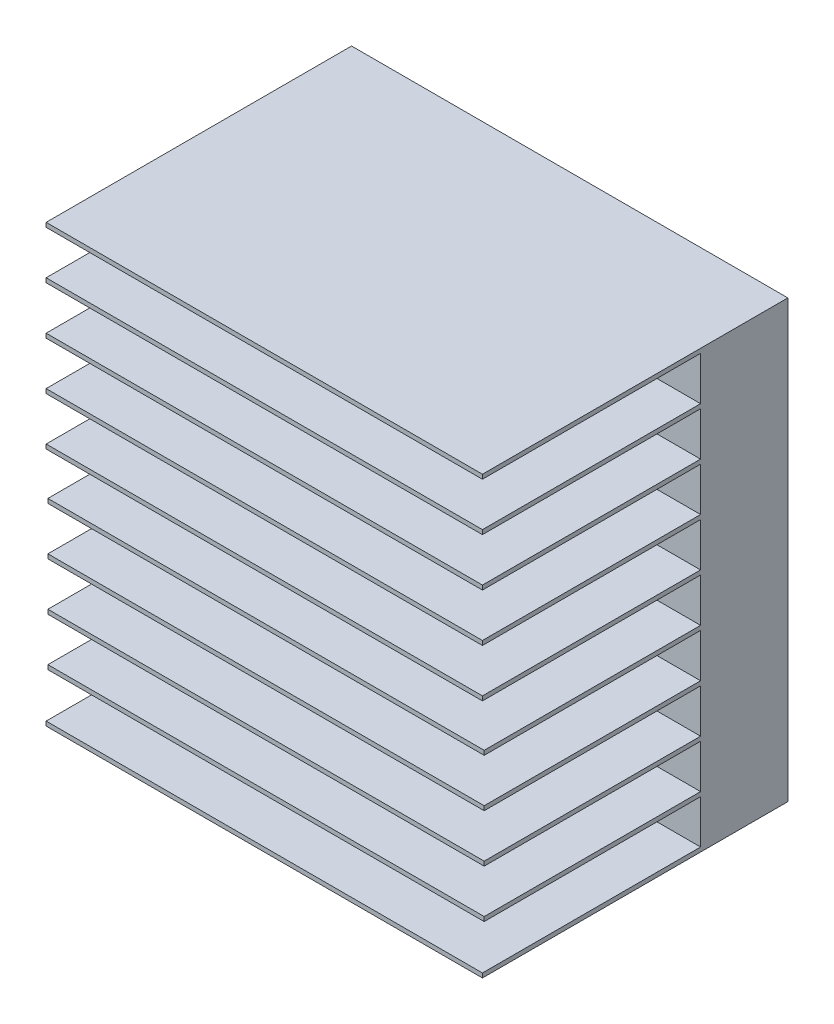
SolidWorks part; units mm, degrees
ref_plane "Front Plane" through (0, 0, 0) normal (0, 0, 1) x (1, 0, 0)
ref_plane "Top Plane" through (0, 0, 0) normal (0, 1, 0) x (1, 0, 0)
ref_plane "Right Plane" through (0, 0, 0) normal (1, 0, 0) x (0, 0, -1)
sketch "Sketch2" plane through (0, 0, 0) normal (0, 0, 1) x (1, 0, 0)
  line L1 (0, 0) -> (25.4, 0)
  line L2 (0, 0) -> (0, 25.4)
  line L3 (0, 25.4) -> (25.4, 25.4)
  line L4 (25.4, 0) -> (25.4, 25.4)
  dimension "D1" = 25.4
  dimension "D2" = 25.4
extrude "Boss-Extrude1" add sketch "Sketch2" along normal blind 5.08
sketch "Sketch3" plane through (0, 0, 5.08) normal (0, 0, 1) x (1, 0, 0)
  line L0 (25.4, 0) -> (25.4, 25.4) construction
  line L1 (0, 25.4) -> (25.4, 25.4)
  line L2 (0, 25.4) -> (0, 25.146)
  line L3 (0, 25.146) -> (25.4, 25.146)
  line L4 (25.4, 25.4) -> (25.4, 25.146)
  dimension "D1" = 0.254
extrude "Boss-Extrude2" add sketch "Sketch3" along normal blind 12.7
sketch "Sketch4" plane through (0, 0, 5.08) normal (0, 0, 1) x (1, 0, 0)
  line L0 (25.4, 0) -> (25.4, 25.146) construction
  line L1 (0, 25.146) -> (0, 0) construction
  line L2 (0, 0) -> (25.4, 0)
  line L3 (0, 0) -> (0, 0.254)
  line L4 (0, 0.254) -> (25.4, 0.254)
  line L5 (25.4, 0) -> (25.4, 0.254)
  line L6 (0, 22.606) -> (25.4, 22.606)
  line L7 (0, 22.606) -> (0, 22.352)
  line L8 (0, 22.352) -> (25.4, 22.352)
  line L9 (25.4, 22.606) -> (25.4, 22.352)
  line L11 (0, 25.146) -> (25.4, 25.146) construction
  dimension "D1" = 0.254
  dimension "D2" = 0.254
  dimension "D3" = 2.54
sketch "Sketch5" plane through (0, 0, 5.08) normal (0, 0, 1) x (1, 0, 0)
  line L0 (0, 25.146) -> (0, 0) construction
  line L1 (0, 19.812) -> (25.4, 19.812)
  line L2 (0, 19.812) -> (0, 19.558)
  line L3 (0, 19.558) -> (25.4, 19.558)
  line L4 (25.4, 19.812) -> (25.4, 19.558)
  line L5 (25.4, 0) -> (25.4, 25.146) construction
  line L7 (0, 17.018) -> (25.4, 17.018)
  line L8 (0, 17.018) -> (0, 16.764)
  line L9 (0, 16.764) -> (25.4, 16.764)
  line L10 (25.4, 17.018) -> (25.4, 16.764)
  line L11 (0, 14.224) -> (25.4, 14.224)
  line L12 (0, 14.224) -> (0, 13.97)
  line L13 (0, 13.97) -> (25.4, 13.97)
  line L14 (25.4, 14.224) -> (25.4, 13.97)
  dimension "D1" = 0.254
  dimension "D2" = 2.54
  dimension "D3" = 0.254
  dimension "D4" = 2.54
  dimension "D5" = 0.254
  dimension "D6" = 2.54
sketch "Sketch6" plane through (0, 0, 5.08) normal (0, 0, 1) x (1, 0, 0)
  line L0 (0, 25.146) -> (0, 0) construction
  line L1 (0, 11.43) -> (25.4, 11.43)
  line L2 (0, 11.43) -> (0, 11.176)
  line L3 (0, 11.176) -> (25.4, 11.176)
  line L4 (25.4, 11.43) -> (25.4, 11.176)
  line L5 (25.4, 0) -> (25.4, 25.146) construction
  line L7 (0, 8.636) -> (25.4, 8.636)
  line L8 (0, 8.636) -> (0, 8.382)
  line L9 (0, 8.382) -> (25.4, 8.382)
  line L10 (25.4, 8.636) -> (25.4, 8.382)
  line L11 (0, 5.842) -> (25.4, 5.842)
  line L12 (0, 5.842) -> (0, 5.588)
  line L13 (0, 5.588) -> (25.4, 5.588)
  line L14 (25.4, 5.842) -> (25.4, 5.588)
  line L15 (0, 3.048) -> (25.4, 3.048)
  line L16 (0, 3.048) -> (0, 2.794)
  line L17 (0, 2.794) -> (25.4, 2.794)
  line L18 (25.4, 3.048) -> (25.4, 2.794)
  dimension "D1" = 0.254
  dimension "D2" = 2.54
  dimension "D3" = 0.254
  dimension "D4" = 2.54
  dimension "D5" = 0.254
  dimension "D6" = 2.54
  dimension "D7" = 0.254
  dimension "D8" = 2.54
extrude "Boss-Extrude3" add sketch "Sketch6" along normal blind 12.5984
extrude "Boss-Extrude4" add sketch "Sketch5" along normal blind 12.7
extrude "Boss-Extrude5" add sketch "Sketch4" along normal blind 12.7
